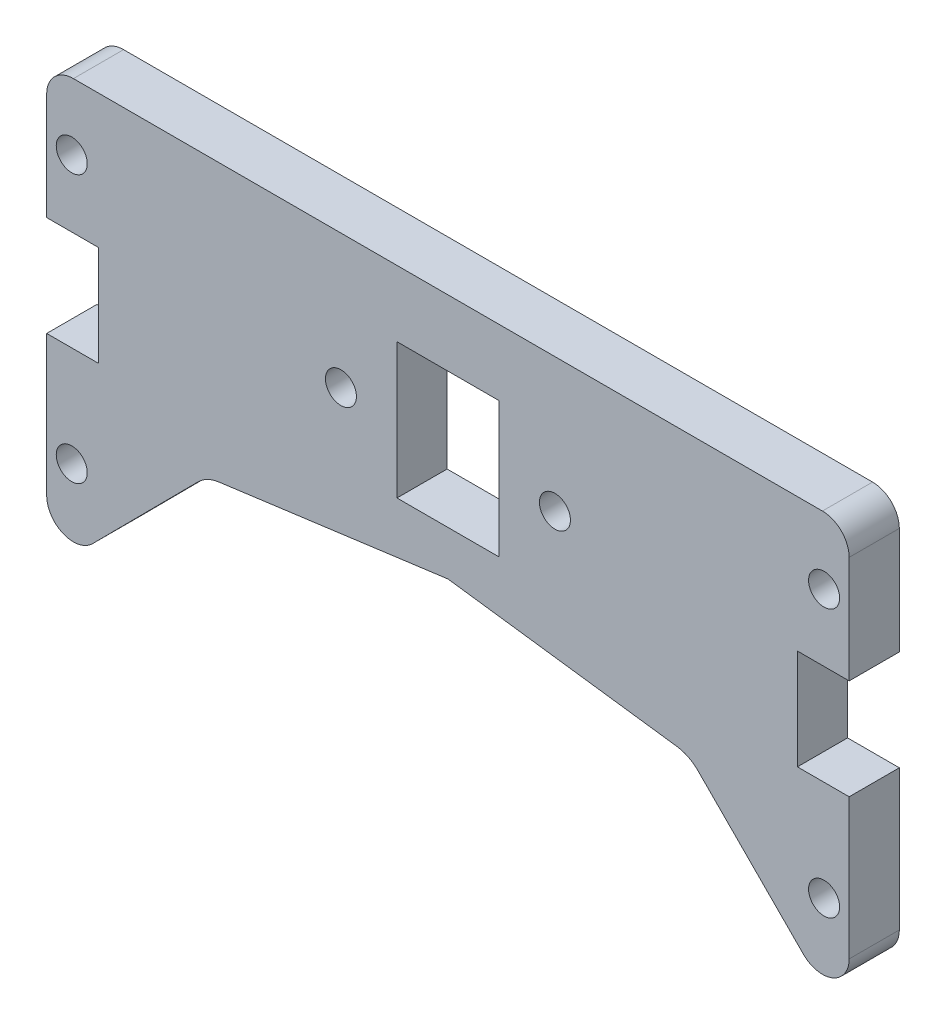
SolidWorks part; units mm, degrees
ref_plane "Front Plane" through (0, 0, 0) normal (0, 0, 1) x (1, 0, 0)
ref_plane "Top Plane" through (0, 0, 0) normal (0, 1, 0) x (1, 0, 0)
ref_plane "Right Plane" through (0, 0, 0) normal (1, 0, 0) x (0, 0, -1)
sketch "Sketch2" plane through (0, 0, 0) normal (0, 0, 1) x (1, 0, 0)
  line L0 (0, -1000) -> (0, 49000) construction
  line L1 (-35.56, -19.05) -> (35.56, -19.05) construction
  line L2 (-38.1, -16.51) -> (-38.1, -3.175)
  line L3 (-35.56, 19.05) -> (35.56, 19.05)
  line L4 (38.1, -16.51) -> (38.1, -3.175)
  line L5 (-38.1, -19.05) -> (38.1, 19.05) construction
  line L6 (-38.1, 19.05) -> (38.1, -19.05) construction
  line L7 (-33.7574, -18.2994) -> (-23.7409, -8.209)
  line L8 (-21.7452, -7.2181) -> (0, -4.3161)
  line L9 (21.7452, -7.2181) -> (0, -4.3161)
  line L10 (33.7574, -18.2994) -> (23.7409, -8.209)
  line L11 (33.1851, -3.175) -> (38.1, -3.175)
  line L12 (33.1851, 6.35) -> (33.1851, -3.175)
  line L13 (-16.51, 12.685) -> (-4.7625, 12.685) construction
  line L14 (-16.51, 12.685) -> (-16.51, -0.015) construction
  line L15 (-38.1, 6.35) -> (-33.1851, 6.35)
  line L16 (-4.8387, 12.7762) -> (4.8387, 12.7762)
  line L17 (-4.8387, 12.7762) -> (-4.8387, -0.0762)
  line L18 (-4.8387, -0.0762) -> (4.8387, -0.0762)
  line L19 (4.8387, 12.7762) -> (4.8387, -0.0762)
  line L20 (-33.1851, 6.35) -> (-33.1851, -3.175)
  line L21 (-33.1851, -3.175) -> (-38.1, -3.175)
  line L22 (38.1, 6.35) -> (33.1851, 6.35)
  line L23 (-38.1, 6.35) -> (-38.1, 16.51)
  line L24 (38.1, 6.35) -> (38.1, 16.51)
  arc A0 (-33.7574, -18.2994) -> (-38.1, -16.51) centre (-35.56, -16.51) cw
  arc A1 (33.7574, -18.2994) -> (38.1, -16.51) centre (35.56, -16.51) ccw
  arc A2 (35.56, 19.05) -> (38.1, 16.51) centre (35.56, 16.51) cw
  arc A3 (-38.1, 16.51) -> (-35.56, 19.05) centre (-35.56, 16.51) cw
  circle A4 centre (-35.7188, 12.7) radius 1.4732
  circle A5 centre (-35.7188, -12.7) radius 1.4732
  circle A6 centre (35.7188, -12.7) radius 1.4732
  circle A7 centre (35.7188, 12.7) radius 1.4732
  arc A9 (-23.7409, -8.209) -> (-21.7452, -7.2181) centre (-21.288, -10.644) cw
  arc A10 (21.7452, -7.2181) -> (23.7409, -8.209) centre (21.288, -10.644) cw
  circle A11 centre (-10.16, 6.335) radius 1.4732
  circle A12 centre (10.16, 6.335) radius 1.4732
  point P0 (0, 0)
  point P35 (0, -4.3161)
  point P38 (-22.9118, -7.3738)
  point P41 (22.9118, -7.3738)
  point P52 (0, 12.7762)
  dimension "D2" = 2.54
  dimension "D5" = 2.9464
  dimension "D6" = 6.35
  dimension "D11" = 2.9464
  dimension "D1" = 76.2
  dimension "D3" = 38.1
  dimension "D4" = 2.3813
  dimension "D7" = 6.35
  dimension "D8" = 31.75
  dimension "D9" = 6.35
  dimension "D10" = 6.2738
  dimension "D12" = 12.8524
  dimension "D13" = 9.6774
  dimension "D14" = 12.7
  dimension "D15" = 9.525
  dimension "D16" = 4.9149
extrude "Boss-Extrude1" add sketch "Sketch2" along normal blind 4.7625
